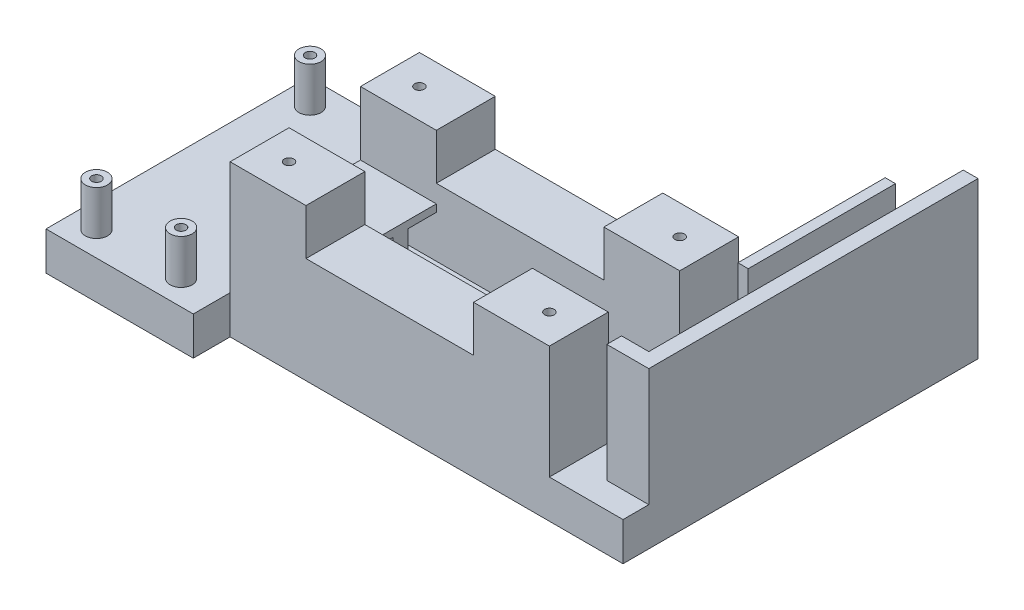
SolidWorks part; units mm, degrees
ref_plane "前视基准面" through (0, 0, 0) normal (0, 0, 1) x (1, 0, 0)
ref_plane "上视基准面" through (0, 0, 0) normal (0, 1, 0) x (1, 0, 0)
ref_plane "右视基准面" through (0, 0, 0) normal (1, 0, 0) x (0, 0, -1)
sketch "草图1" plane through (0, 0, 0) normal (0, 0, 1) x (1, 0, 0)
  line L1 (-42.1231, 25.5984) -> (44.5769, 25.5984)
  line L2 (-42.1231, 25.5984) -> (-42.1231, 5.5984)
  line L3 (-42.1231, 5.5984) -> (44.5769, 5.5984)
  line L4 (44.5769, 25.5984) -> (44.5769, 5.5984)
  line L5 (-21.5231, 25.5984) -> (23.9769, 25.5984)
  line L6 (-21.5231, 25.5984) -> (-21.5231, 13.1284)
  line L7 (-21.5231, 13.1284) -> (23.9769, 13.1284)
  line L8 (23.9769, 25.5984) -> (23.9769, 13.1284)
  dimension "D1" = 86.7
  dimension "D2" = 20
  dimension "D3" = 45.5
  dimension "D4" = 20.6
  dimension "D5" = 20.6
  dimension "D6" = 12.47
extrude "凸台-拉伸1" add sketch "草图1" along normal blind 16 contours L1 L8 L7 L6 L2 L3 L4
sketch "草图2" plane through (0, 25.5984, 0) normal (0, 1, 0) x (1, 0, 0)
  line L0 (23.9769, -8) -> (28.5769, -8) construction
  line L1 (23.9769, -16) -> (23.9769, 0) construction
  line L2 (28.5769, -8) -> (28.5769, 0) construction
  line L3 (23.9769, 0) -> (44.5769, 0) construction
  line L4 (28.5769, 0) -> (28.5769, -16) construction
  line L5 (23.9769, -16) -> (44.5769, -16) construction
  line L7 (28.5769, 0) -> (44.5769, -16) construction
  line L8 (44.5769, 0) -> (28.5769, -16) construction
  point P16 (36.5769, -8)
  dimension "D1" = 4.6
hole_wizard "Ø1.0mm 暗销孔1" positions "草图2" profile "草图3" hole size "Ø1.0" standard "GB" end condition through all
sketch "草图3" plane through (36.5769, 25.5984, 8) normal (1, 0, 0) x (0, 0, 1)
  line L0 (0, 0) -> (0, 20)
  line L1 (0, 20) -> (1.3, 20)
  line L2 (1.3, 20) -> (1.3, 0)
  line L5 (1.3, 0) -> (0, 0)
  line L11 (0, -6.35) -> (0, 107.95) construction
  dimension "通孔孔直径" = 2.6
  dimension "通孔孔深度" = 20
sketch "草图4" plane through (0, 25.5984, 0) normal (0, 1, 0) x (1, 0, 0)
  line L0 (-21.5231, -8) -> (-26.1231, -8) construction
  line L1 (-21.5231, -16) -> (-21.5231, 0) construction
  line L2 (-26.1231, -8) -> (-26.1231, 0) construction
  line L3 (-42.1231, 0) -> (-21.5231, 0) construction
  line L4 (-26.1231, 0) -> (-26.1231, -16) construction
  line L5 (-42.1231, -16) -> (-21.5231, -16) construction
  line L6 (-42.1231, 0) -> (-26.1231, -16) construction
  line L7 (-26.1231, -16) -> (-26.1231, 0) construction
  line L8 (-26.1231, 0) -> (-42.1231, -16) construction
  point P15 (-34.1231, -8)
  dimension "D1" = 4.6
hole_wizard "Ø1.0mm 暗销孔2" positions "草图4" profile "草图5" hole size "Ø1.0" standard "GB" end condition through all
sketch "草图5" plane through (-34.1231, 25.5984, 8) normal (1, 0, 0) x (0, 0, 1)
  line L0 (0, 0) -> (0, 20)
  line L1 (0, 20) -> (1.3, 20)
  line L2 (1.3, 20) -> (1.3, 0)
  line L5 (1.3, 0) -> (0, 0)
  line L11 (0, -6.35) -> (0, 107.95) construction
  dimension "通孔孔直径" = 2.6
  dimension "通孔孔深度" = 20
sketch "草图7" plane through (0, 25.5984, 0) normal (0, 1, 0) x (1, 0, 0)
sketch "草图8" plane through (0, 5.5984, 0) normal (0, -1, 0) x (1, 0, 0)
  line L1 (-42.1231, 16) -> (44.5769, 16)
  line L2 (-42.1231, 16) -> (-42.1231, 0)
  line L3 (-42.1231, 0) -> (44.5769, 0)
  line L4 (44.5769, 16) -> (44.5769, 0)
extrude "凸台-拉伸2" add sketch "草图8" along normal blind 21.2
sketch "草图9" plane through (0, 0, 0) normal (0, 0, -1) x (-1, 0, 0)
  line L0 (42.1231, 25.5984) -> (42.1231, -15.6016) construction
  line L1 (-44.5769, -15.6016) -> (42.1231, -15.6016)
  line L2 (-44.5769, -15.6016) -> (-44.5769, -5.2016)
  line L3 (-44.5769, -5.2016) -> (42.1231, -5.2016)
  line L4 (42.1231, -15.6016) -> (42.1231, -5.2016)
  dimension "D1" = 10.4
extrude "凸台-拉伸3" add sketch "草图9" along normal blind 9.7
sketch "草图15" plane through (0, -5.2016, 0) normal (0, 1, 0) x (1, 0, 0)
  line L5 (-42.1231, 9.7) -> (-21.5231, 9.7)
  line L6 (-42.1231, 9.7) -> (-42.1231, 7.7)
  line L7 (-42.1231, 7.7) -> (-21.5231, 7.7)
  line L8 (-21.5231, 9.7) -> (-21.5231, 7.7)
  dimension "D1" = 2
extrude "凸台-拉伸8" add sketch "草图15" along normal blind 13.5
sketch "草图16" plane through (0, 0, -9.7) normal (0, 0, -1) x (-1, 0, 0)
  line L0 (42.1231, -15.6016) -> (42.1231, 8.2984) construction
  line L1 (21.5231, 8.2984) -> (42.1231, 8.2984)
  line L2 (21.5231, 8.2984) -> (21.5231, 6.2984)
  line L3 (21.5231, 6.2984) -> (42.1231, 6.2984)
  line L4 (42.1231, 8.2984) -> (42.1231, 6.2984)
  dimension "D1" = 2
extrude "凸台-拉伸9" add sketch "草图16" against normal blind 10.5
mirror "镜向20" about plane through (0, 0, -9.7) normal (0, 0, 1) of "Ø1.0mm 暗销孔2", "Ø1.0mm 暗销孔1", "凸台-拉伸3", "凸台-拉伸1", "凸台-拉伸2", "凸台-拉伸8", "凸台-拉伸9"
sketch "草图19" plane through (44.5769, 0, 0) normal (1, 0, 0) x (0, 0, -1)
  line L0 (35.4, 25.5984) -> (35.4, -15.6016) construction
  line L1 (-16, -15.6016) -> (35.4, -15.6016)
  line L2 (-16, -15.6016) -> (-16, -5.2016)
  line L3 (-16, -5.2016) -> (35.4, -5.2016)
  line L4 (35.4, -15.6016) -> (35.4, -5.2016)
  line L5 (19.4, -5.2016) -> (0, -5.2016) construction
  dimension "D1" = 0
  dimension "D2" = 10.4
extrude "凸台-拉伸10" add sketch "草图19" along normal blind 20
sketch "草图25" plane through (0, 0, -35.4) normal (0, 0, -1) x (-1, 0, 0)
  line L0 (-64.5769, -15.6016) -> (42.1231, -15.6016) construction
  line L1 (-64.5769, -5.2016) -> (-44.5769, -5.2016)
  line L2 (-64.5769, -5.2016) -> (-64.5769, -15.6016)
  line L3 (-64.5769, -15.6016) -> (-44.5769, -15.6016)
  line L4 (-44.5769, -5.2016) -> (-44.5769, -15.6016)
extrude "凸台-拉伸11" add sketch "草图25" along normal blind 45
sketch "草图26" plane through (0, -5.2016, 0) normal (0, 1, 0) x (1, 0, 0)
  line L0 (44.5769, 0) -> (64.5769, 0) construction
  line L1 (64.5769, 80.4) -> (64.5769, -16) construction
  line L2 (44.5769, 80.4) -> (64.5769, 80.4) construction
  line L7 (53.1769, -9) -> (64.5769, -9)
  line L8 (53.1769, -9) -> (53.1769, -5)
  line L9 (53.1769, -5) -> (60.5769, -5)
  line L10 (64.5769, -9) -> (64.5769, -5)
  line L12 (64.5769, -5) -> (64.5769, 80.4)
  line L13 (64.5769, 80.4) -> (60.5769, 80.4)
  line L14 (60.5769, -5) -> (60.5769, 80.4)
  line L15 (53.1769, -5) -> (53.1769, 28) construction
  line L29 (53.1769, 28) -> (54.5769, 28)
  line L31 (53.1769, 68) -> (54.5769, 68)
  line L32 (54.5769, 28) -> (54.5769, 68)
  line L36 (53.1769, 68) -> (53.1769, 83.3786) construction
  line L37 (53.1769, 28) -> (51.7769, 28)
  line L39 (53.1769, 68) -> (51.7769, 68)
  line L40 (51.7769, 28) -> (51.7769, 68)
  dimension "D1" = 4
  dimension "D2" = 5
  dimension "D3" = 4
  dimension "D4" = 7.4
  dimension "D5" = 1.4
  dimension "D6" = 28
  dimension "D7" = 1.4
  dimension "D8" = 40
  dimension "D9" = 6
extrude "凸台-拉伸12" add sketch "草图26" along normal blind 32
sketch "草图28" plane through (0, -5.2016, 0) normal (0, 1, 0) x (1, 0, 0)
  line L1 (60.5769, 80.4) -> (54.5769, 80.4)
  line L2 (60.5769, 80.4) -> (60.5769, 28)
  line L4 (54.5769, 80.4) -> (54.5769, 28)
  line L7 (54.5769, -5) -> (60.5769, -5)
  line L8 (60.5769, 28) -> (60.5769, -5)
  line L9 (54.5769, 28) -> (52.5769, 28)
  line L11 (54.5769, -5) -> (52.5769, -5)
  line L12 (52.5769, 28) -> (52.5769, -5)
  dimension "D1" = 2
  dimension "D2" = 6
  dimension "D3" = 33
  dimension "D4" = 6
extrude "切除-拉伸1" cut sketch "草图28" against normal blind 5
sketch "草图29" plane through (-42.1231, 0, 0) normal (-1, 0, 0) x (0, 0, 1)
  line L0 (-35.4, 25.5984) -> (-35.4, -15.6016) construction
  line L1 (-35.4, -5.1986) -> (16, -5.1986)
  line L2 (-35.4, -5.1986) -> (-35.4, -15.6016)
  line L3 (-35.4, -15.6016) -> (16, -15.6016)
  line L4 (16, -5.1986) -> (16, -15.6016)
extrude "凸台-拉伸13" add sketch "草图29" along normal blind 40
sketch "草图32" plane through (0, 0, -35.4) normal (0, 0, -1) x (-1, 0, 0)
  line L1 (42.1231, -5.1986) -> (82.1231, -5.1986)
  line L2 (42.1231, -5.1986) -> (42.1231, -15.6016)
  line L3 (42.1231, -15.6016) -> (82.1231, -15.6016)
  line L4 (82.1231, -5.1986) -> (82.1231, -15.6016)
extrude "凸台-拉伸14" add sketch "草图32" along normal blind 10
sketch "草图33" plane through (0, 0, 16) normal (0, 0, 1) x (1, 0, 0)
  line L0 (64.5769, -15.6016) -> (-82.1231, -15.6016) construction
  line L1 (-82.1231, -5.1986) -> (-42.1231, -5.1986)
  line L2 (-82.1231, -5.1986) -> (-82.1231, -15.6016)
  line L3 (-82.1231, -15.6016) -> (-42.1231, -15.6016)
  line L4 (-42.1231, -5.1986) -> (-42.1231, -15.6016)
extrude "凸台-拉伸15" add sketch "草图33" along normal blind 10
sketch "草图34" plane through (0, -5.1986, 0) normal (0, 1, 0) x (1, 0, 0)
  line L0 (-42.1231, 9.7) -> (-82.1231, 9.7) construction
  line L1 (-55.1231, 38.7) -> (-72.1231, 38.7)
  line L2 (-52.1231, 35.7) -> (-52.1231, -16.3)
  line L3 (-55.1231, -19.3) -> (-72.1231, -19.3)
  line L4 (-75.1231, 35.7) -> (-75.1231, -16.3)
  line L5 (-42.1231, 7.7) -> (-42.1231, 11.7) construction
  line L6 (-82.1231, -26) -> (-82.1231, 45.4) construction
  line L7 (-42.1231, 11.7) -> (-42.1231, 19.4) construction
  circle A0 centre (-52.1231, 38.7) radius 3
  circle A1 centre (-52.1231, -19.3) radius 3
  circle A2 centre (-75.1231, 38.7) radius 3
  circle A3 centre (-75.1231, -19.3) radius 3
  dimension "D4" = 6
  dimension "D5" = 6
  dimension "D7" = 6
  dimension "D8" = 6
  dimension "D1" = 23
  dimension "D2" = 58
  dimension "D3" = 29
  dimension "D6" = 10
extrude "凸台-拉伸16" add sketch "草图34" along normal blind 12 contours A0 | A2 | A1 | A3
sketch "草图35" plane through (0, 6.8014, 0) normal (0, 1, 0) x (1, 0, 0)
  point P0 (-52.1231, 38.7)
hole_wizard "Ø1.0mm 暗销孔3" positions "草图35" profile "草图36" hole size "Ø1.0" standard "GB" end condition through all
sketch "草图36" plane through (-52.1231, 6.8014, -38.7) normal (1, 0, 0) x (0, 0, 1)
  line L0 (0, 0) -> (0, 22.403)
  line L1 (0, 22.403) -> (1.3, 22.403)
  line L2 (1.3, 22.403) -> (1.3, 0)
  line L5 (1.3, 0) -> (0, 0)
  line L11 (0, -6.35) -> (0, 107.95) construction
  dimension "通孔孔直径" = 2.6
  dimension "通孔孔深度" = 22.403
sketch "草图37" plane through (0, 6.8014, 0) normal (0, 1, 0) x (1, 0, 0)
  line L0 (-75.1231, 41.7) -> (-75.1231, 35.7) construction
  line L1 (-75.1231, 35.7) -> (-72.1231, 38.7) construction
  line L2 (-72.1231, 38.7) -> (-78.1231, 38.7) construction
  line L3 (-75.1231, -16.3) -> (-75.1231, -22.3) construction
  line L4 (-75.1231, -22.3) -> (-72.1231, -19.3) construction
  line L5 (-72.1231, -19.3) -> (-78.1231, -19.3) construction
  line L6 (-52.1231, -16.3) -> (-52.1231, -22.3) construction
  line L7 (-52.1231, -22.3) -> (-49.1231, -19.3) construction
  line L8 (-49.1231, -19.3) -> (-55.1231, -19.3) construction
  circle A0 centre (-75.1231, 38.7) radius 3 construction
  circle A1 centre (-75.1231, 38.7) radius 3 construction
  circle A2 centre (-75.1231, -19.3) radius 3 construction
  circle A3 centre (-75.1231, -19.3) radius 3 construction
  circle A4 centre (-52.1231, -19.3) radius 3 construction
  circle A5 centre (-52.1231, -19.3) radius 3 construction
  point P29 (-75.1231, 38.7)
  point P31 (-75.1231, -19.3)
  point P33 (-52.1231, -19.3)
hole_wizard "Ø1.0mm 暗销孔4" positions "草图37" profile "草图38" hole size "Ø1.0" standard "GB" end condition through all
sketch "草图38" plane through (-52.1231, 6.8014, 19.3) normal (1, 0, 0) x (0, 0, 1)
  line L0 (0, 0) -> (0, 22.403)
  line L1 (0, 22.403) -> (1.3, 22.403)
  line L2 (1.3, 22.403) -> (1.3, 0)
  line L5 (1.3, 0) -> (0, 0)
  line L11 (0, -6.35) -> (0, 107.95) construction
  dimension "通孔孔直径" = 2.6
  dimension "通孔孔深度" = 22.403
sketch "草图39" plane through (0, -5.1986, 0) normal (0, 1, 0) x (1, 0, 0)
  line L0 (-75.1231, 38.7) -> (-52.1231, 38.7) construction
  line L1 (-52.1231, 38.7) -> (-52.1231, -19.3) construction
